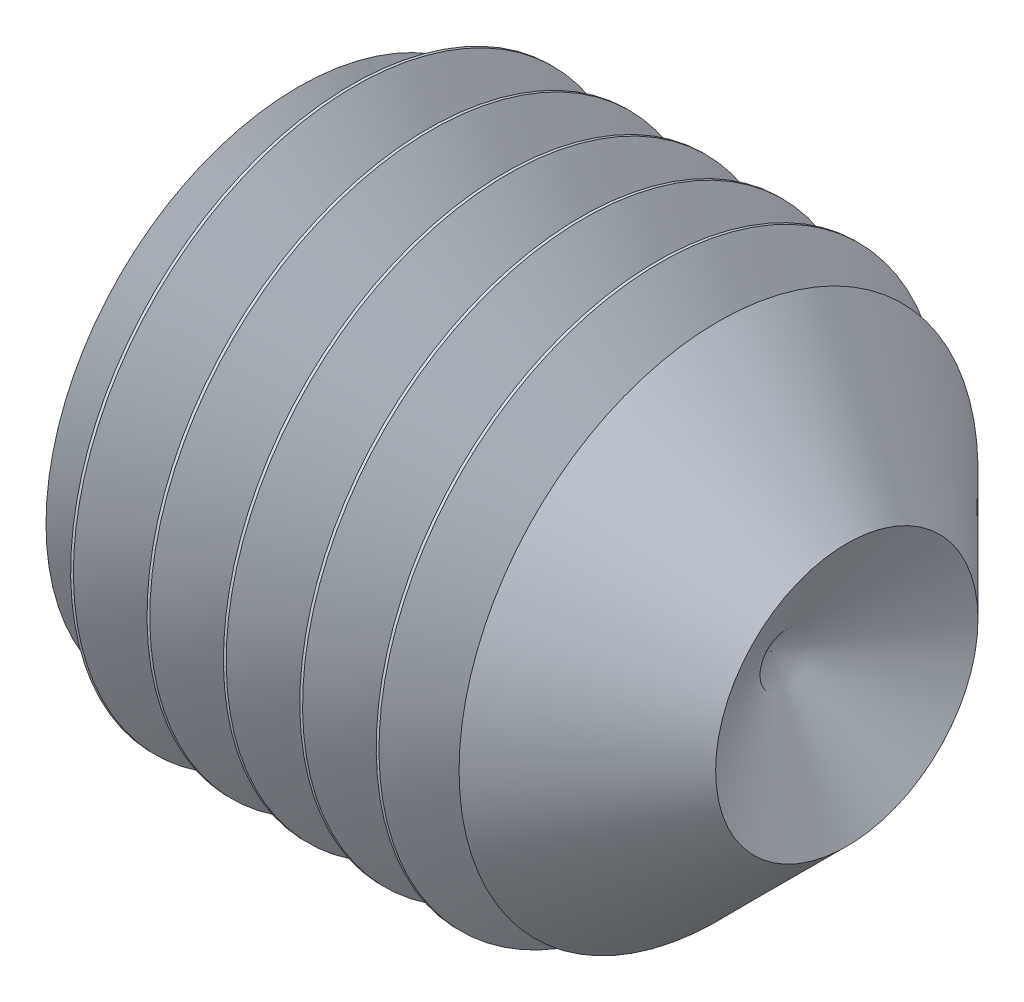
SolidWorks part; units mm, degrees
revolve "BaseBody" add sketch "BodySke" angle 360 about L5
sketch "BodySke" plane through (0, 0, 0) normal (0, 0, 1) x (1, 0, 0)
  line L0 (0, 0) -> (0, 1.2195)
  line L1 (0, 1.2195) -> (0.1619, 1.5)
  line L2 (0.1619, 1.5) -> (2.2, 1.5)
  line L3 (2.2, 1.5) -> (3, 0.7)
  line L4 (2.5959, 0) -> (0, 0)
  line L5 (-12.7, 0) -> (88.9, 0) construction
  line L6 (2.5959, 0) -> (3, 0.7)
  line L7 (3, 0.7) -> (3, 10.225) construction
  line L8 (0, -1.2195) -> (0.1619, -1.5) construction
  line L9 (2.5959, 0) -> (3, -0.7) construction
  line L10 (2.2, -1.5) -> (3, -0.7) construction
  line L11 (0.25, 15.875) -> (0.25, -3.175) construction
  dimension "Diameter" = 3
  dimension "Drive_ch_ang" = 60
  dimension "Minor_dia" = 2.439
  dimension "Cup_ang" = 120
  dimension "Cup_dia" = 1.4
  dimension "Length" = 3
  dimension "Cup_nose_ang" = 45
  dimension "Advance" = 0.5
cosmetic thread "ThreadCosmetic" [suppressed] parameters "Thread_minor"=2.439
ref_plane "Plane1" through (0, 0, 0) normal (0, 0, 1) x (1, 0, 0)
ref_plane "Plane2" through (0, 0, 0) normal (0, 1, 0) x (1, 0, 0)
ref_plane "Plane3" through (0, 0, 0) normal (1, 0, 0) x (0, 0, -1)
sketch "Sketch2" plane through (0, 0, 0) normal (-1, 0, 0) x (0, 0, 1)
  line L0 (0.433, 0.75) -> (-0.433, 0.75)
  line L1 (-0.433, 0.75) -> (-0.866, 0)
  line L2 (0.433, 0.75) -> (0.866, 0)
  line L3 (0.433, -0.75) -> (0.866, 0)
  line L4 (0.433, -0.75) -> (-0.433, -0.75)
  line L5 (-0.433, -0.75) -> (-0.866, 0)
  dimension "Hex_size" = 1.5
  dimension "D2" = 0.75
  dimension "D3" = 0.75
extrude "Hex" cut sketch "Sketch2" against normal blind 2
sketch "ThdSchSke" plane through (0, 0, 0) normal (0, 0, 1) x (1, 0, 0)
  line L0 (0.1619, -1.2195) -> (-0.0345, -1.5)
  line L1 (0.1619, -1.2195) -> (0.3584, -1.5)
  line L2 (0.3584, -1.5) -> (0.3584, -1.875)
  line L3 (-3.175, 0) -> (5.1513, 0) construction
  line L4 (0.1619, 1.5) -> (0.1619, -1.5) construction
  line L5 (0.3584, -1.875) -> (-0.0345, -1.875)
  line L6 (-0.0345, -1.875) -> (-0.0345, -1.5)
  dimension "Thread_minor" = 2.439
  dimension "Diameter" = 3
revolve "ThreadSchematic" cut sketch "ThdSchSke" angle 360 about L3
pattern_linear "ThdSchPat" count 6 spacing 0.4076 along (1, 0, 0) of "ThreadSchematic"
equation "\"D2@Sketch2\" = \"Hex_size@Sketch2\" / 2"
equation "\"D3@Sketch2\" = \"Hex_size@Sketch2\" / 2"
equation "\"Thread_minor@ThreadCosmetic\" = \"Minor_dia@BodySke\""
equation "\"Thread_minor@ThdSchSke\" = \"Thread_minor@ThreadCosmetic\""
equation "\"Diameter@ThdSchSke\" = \"Diameter@BodySke\""
equation "\"Overcut@ThdSchSke\" = \"Diameter@BodySke\" * 1.25"
equation "\"Num_threads@ThdSchPat\" = int( (\"Length@BodySke\" - ( ( ( \"Diameter@BodySke\" - \"Minor_dia@BodySke\" ) * 0.5 ) / tan( \"Drive_ch_ang@BodySke\" * 0.017453292 ) ) - ( ( ( \"Diameter@BodySke\" - \"Cup_dia@BodySke\" ) * 0.5 ) * tan( \"Cup_nose_ang@BodySke\" * 0.017453292 ) ) ) / \"Advance@BodySke\" + 0.999 )  + 1"
equation "\"Advance@ThdSchPat\" = (\"Length@BodySke\" - ( ( ( \"Diameter@BodySke\" - \"Minor_dia@BodySke\" ) * 0.5 ) / tan( \"Drive_ch_ang@BodySke\" * 0.017453292 ) ) - ( ( ( \"Diameter@BodySke\" - \"Cup_dia@BodySke\" ) * 0.5 ) * tan( \"Cup_nose_ang@BodySke\" * 0.017453292 ) ) ) /  (\"Num_threads@ThdSchPat\" - 1) 'relax it"
equation "' \"Num_threads@ThdSchPat\" = \"Num_threads@ThdSchPat\" - sgn( \"Num_threads@ThdSchPat\" - 1) '---chamfered tips only---"
